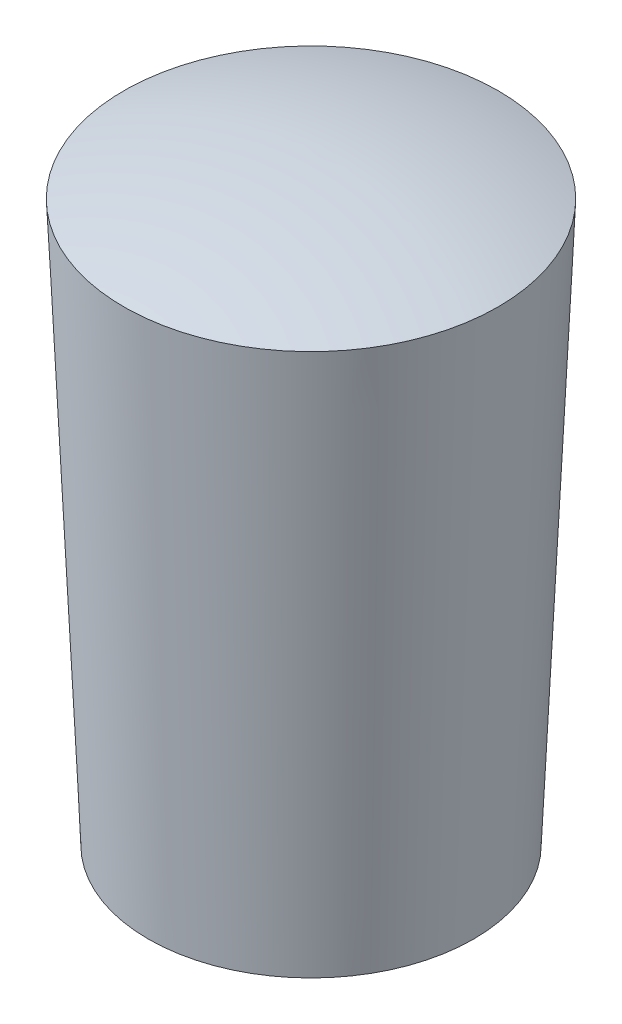
SolidWorks part; units mm, degrees
material "ABS"
ref_plane "Front Plane" through (0, 0, 0) normal (0, 0, 1) x (1, 0, 0)
ref_plane "Top Plane" through (0, 0, 0) normal (0, 1, 0) x (1, 0, 0)
ref_plane "Right Plane" through (0, 0, 0) normal (1, 0, 0) x (0, 0, -1)
sketch "Primary Sketch" plane through (0, 0, 0) normal (0, 0, 1) x (1, 0, 0)
  line L0 (0, 0) -> (0, 82.7407) construction
sketch "Base Sketch" plane through (0, 0, 0) normal (0, 0, 1) x (1, 0, 0)
  line L0 (9.69, 28.9725) -> (8.425, 0)
  line L1 (0, 0) -> (0, 82.7407) construction
  arc A0 (9.69, 28.9725) -> (0, 30.55) centre (0, 0) ccw
  point P3 (0, 0)
  point P5 (0, 30.55)
  point P7 (0, 30.55)
  dimension "D1" = 2.5
  dimension "D2" = 30.55
  dimension "D3" = 8.425
revolve "Base" add sketch "Base Sketch" angle 360 about L0
